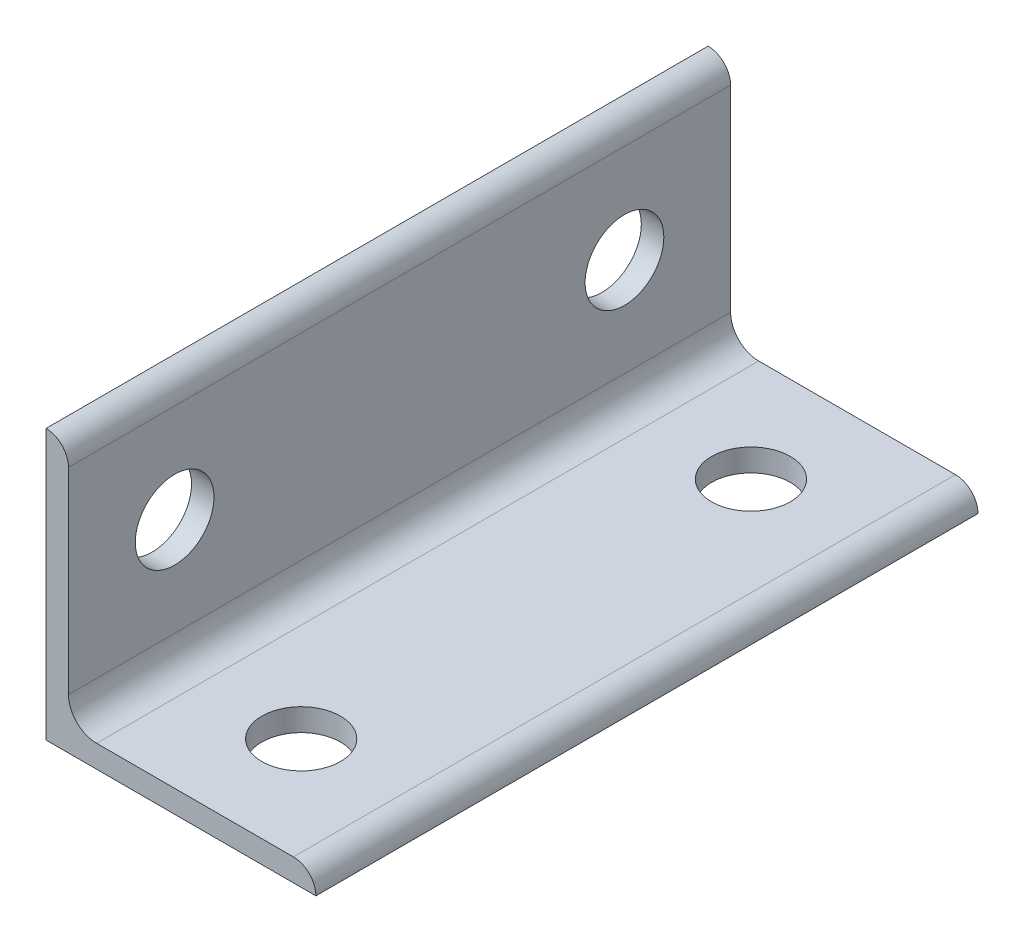
SolidWorks part; units mm, degrees
ref_plane "Front Plane" through (0, 0, 0) normal (0, 0, 1) x (1, 0, 0)
ref_plane "Top Plane" through (0, 0, 0) normal (0, 1, 0) x (1, 0, 0)
ref_plane "Right Plane" through (0, 0, 0) normal (1, 0, 0) x (0, 0, -1)
sketch "Sketch1" plane through (0, 0, 0) normal (0, 0, 1) x (1, 0, 0)
  line L0 (-47.625, 0) -> (-47.625, 76.2)
  line L2 (-47.625, 0) -> (28.575, 0)
  line L3 (22.225, 6.35) -> (-33.3375, 6.35)
  line L4 (-41.275, 69.85) -> (-41.275, 14.2875)
  arc A0 (-41.275, 69.85) -> (-47.625, 76.2) centre (-47.625, 69.85) ccw
  arc A1 (-41.275, 14.2875) -> (-33.3375, 6.35) centre (-33.3375, 14.2875) ccw
  arc A2 (22.225, 6.35) -> (28.575, 0) centre (22.225, 0) cw
extrude "Boss-Extrude1" add sketch "Sketch1" against normal up to surface (186.944 mm away)
sketch "Sketch2" plane through (-41.275, 0, 0) normal (1, 0, 0) x (0, 0, -1)
  line L0 (93.472, 69.85) -> (93.472, 14.2875) construction
  line L1 (186.944, 69.85) -> (0, 69.85) construction
  line L2 (186.944, 14.2875) -> (0, 14.2875) construction
  line L3 (156.972, 42.0688) -> (29.972, 42.0687) construction
  circle A0 centre (156.972, 42.0688) radius 11.1125
  circle A1 centre (29.972, 42.0687) radius 11.1125
  point P8 (93.472, 42.0688)
  dimension "D1" = 22.225
  dimension "D2" = 127
extrude "Cut-Extrude1" cut sketch "Sketch2" against normal up to next
sketch "Sketch3" plane through (0, 6.35, 0) normal (0, 1, 0) x (1, 0, 0)
  line L0 (-33.3375, 93.472) -> (22.225, 93.472) construction
  line L1 (-33.3375, 186.944) -> (-33.3375, 0) construction
  line L2 (22.225, 186.944) -> (22.225, 0) construction
  line L3 (-5.5563, 156.972) -> (-5.5563, 29.972) construction
  line L4 (-5.5563, 156.972) -> (-41.275, 156.972) construction
  line L5 (-41.275, 145.8595) -> (-41.275, 168.0845) construction
  circle A0 centre (-5.5563, 156.972) radius 11.1125
  circle A1 centre (-5.5563, 29.972) radius 11.1125
  point P8 (-5.5563, 93.472)
  dimension "D1" = 22.225
extrude "Cut-Extrude2" cut sketch "Sketch3" against normal up to next
